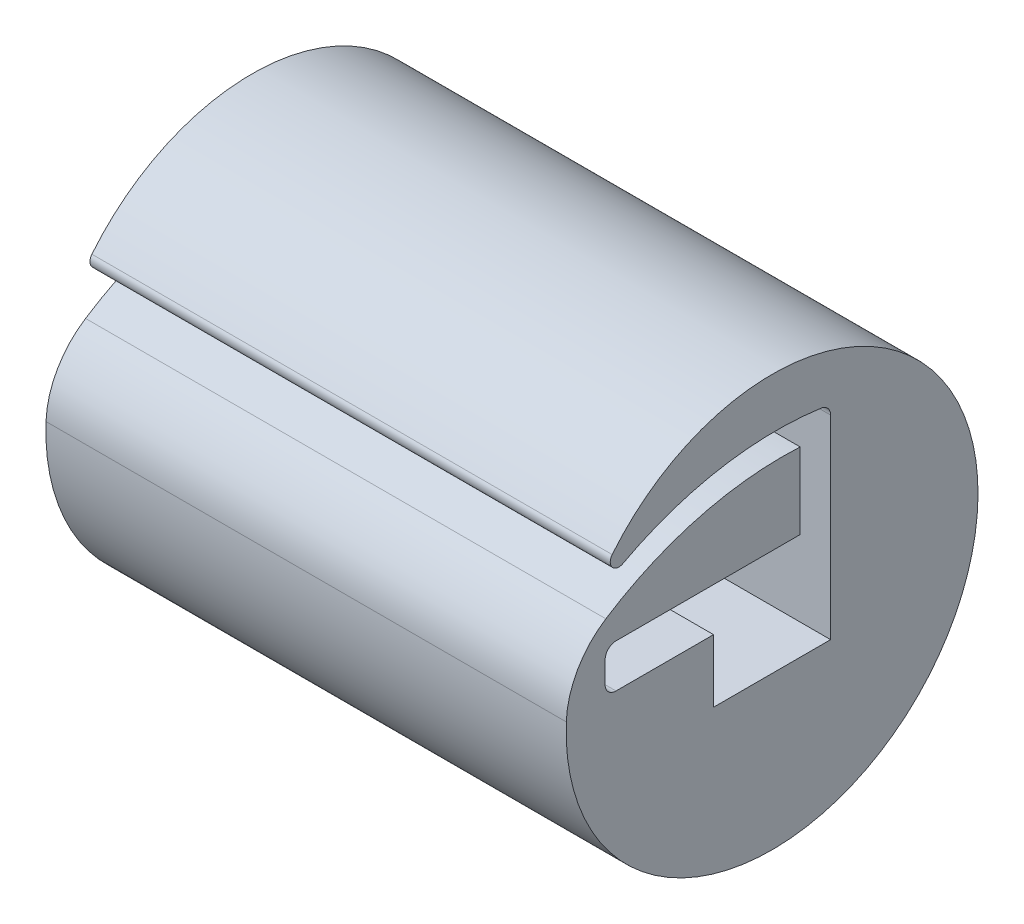
SolidWorks part; units mm, degrees
ref_plane "Front Plane" through (0, 0, 0) normal (0, 0, 1) x (1, 0, 0)
ref_plane "Top Plane" through (0, 0, 0) normal (0, 1, 0) x (1, 0, 0)
ref_plane "Right Plane" through (0, 0, 0) normal (1, 0, 0) x (0, 0, -1)
sketch "Sketch1" plane through (0, 0, 0) normal (1, 0, 0) x (0, 0, -1)
  line L0 (-1.35, 0.225) -> (-1.35, -1.225)
  line L5 (-1.35, -1.225) -> (1.35, -1.225)
  line L6 (-1.35, -1.225) -> (-1.35, 1.225) construction
  line L7 (-1.35, 1.225) -> (1.35, 1.225) construction
  line L8 (1.35, -1.225) -> (1.35, 1.225)
  line L9 (-1.35, -1.225) -> (1.35, 1.225) construction
  line L10 (-1.35, 1.225) -> (1.35, -1.225) construction
  line L11 (-1.35, 1.225) -> (-3.85, 1.225)
  line L12 (-1.35, 1.225) -> (-1.35, 0.225) construction
  line L13 (-1.35, 0.225) -> (-3.85, 0.225)
  line L14 (-3.85, 1.225) -> (-3.85, 0.225)
  line L15 (1.35, 3.475) -> (1.35, 1.225)
  line L16 (1.35, 1.225) -> (0.6485, 1.225) construction
  line L19 (0.6485, 1.225) -> (0.6485, 2.975)
  line L20 (-1.35, 1.225) -> (0.6485, 1.225)
  line L21 (-3.85, 1.225) -> (-4.5893, 1.225) construction
  arc A1 (-4.1967, 2.225) -> (-4.5893, 1.225) centre (0, 0) ccw
  arc A2 (-4.5893, 1.225) -> (0.6485, 2.975) centre (0.2393, -4.5138) cw
  arc A3 (-4.1967, 2.225) -> (1.35, 3.475) centre (0.1025, -3.9205) cw
  circle A5 centre (0, 0) radius 4.75 construction
  circle A6 centre (0, 0) radius 4.75
  dimension "D1" = 9.5
  dimension "D2" = 2.7
  dimension "D3" = 1
  dimension "D5" = 0.7015
  dimension "D6" = 7.5
  dimension "D7" = 7.5
  dimension "D8" = 2.25
  dimension "D4" = 2.5
  dimension "D9" = 1.75
  dimension "D10" = 1
  dimension "D11" = 2.45
extrude "Boss-Extrude2" add sketch "Sketch1" along normal mid plane 12 contours A2 A6 A3 L15 L8 L5 L0 L13 L14 L11 L20 L19
fillet "Fillet1" radius 0.25 3 edges at (0, 0.225, 3.85) (0, 1.225, 3.85) (0, 3.475, -1.35)
fillet "Fillet2" radius 2 1 edges at (0, 1.225, 4.5893)
fillet "Fillet3" radius 0.2 1 edges at (0, 2.225, 4.1967)
